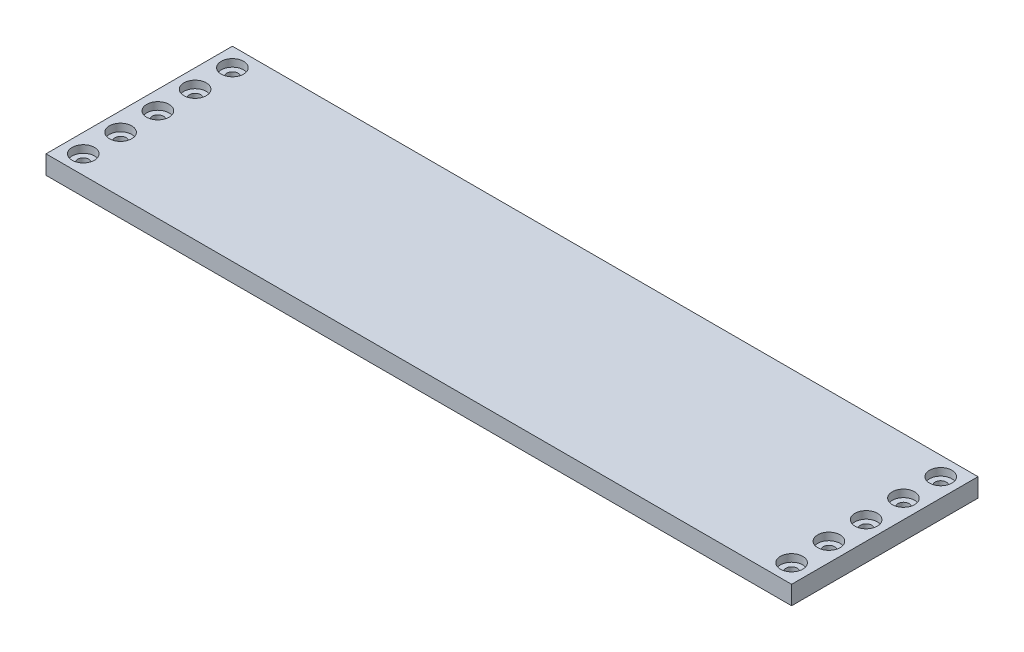
SolidWorks part; units mm, degrees
ref_plane "Front Plane" through (0, 0, 0) normal (0, 0, 1) x (1, 0, 0)
ref_plane "Top Plane" through (0, 0, 0) normal (0, 1, 0) x (1, 0, 0)
ref_plane "Right Plane" through (0, 0, 0) normal (1, 0, 0) x (0, 0, -1)
sketch "Sketch3" plane through (0, 0, 0) normal (0, 1, 0) x (1, 0, 0)
  line L1 (-100, -25) -> (100, -25)
  line L2 (-100, -25) -> (-100, 25)
  line L3 (-100, 25) -> (100, 25)
  line L4 (100, -25) -> (100, 25)
  line L5 (-100, -25) -> (100, 25) construction
  line L6 (-100, 25) -> (100, -25) construction
  point P0 (0, 0)
  dimension "D1" = 50
  dimension "D2" = 200
extrude "Boss-Extrude1" add sketch "Sketch3" along normal blind 5
sketch "Sketch4" plane through (0, 5, 0) normal (0, 1, 0) x (1, 0, 0)
  line L0 (-95, 25) -> (-95, -25) construction
  line L1 (95, 25) -> (95, -25) construction
  line L2 (0, 0) -> (0, 25) construction
  line L4 (100, -25) -> (100, 25)
  line L5 (100, 25) -> (-100, 25)
  line L6 (-100, 25) -> (-100, -25)
  line L7 (-100, -25) -> (100, -25)
  line L8 (100, -25) -> (100, 25)
  line L9 (100, 25) -> (-100, 25)
  line L10 (-100, 25) -> (-100, -25)
  line L11 (-100, -25) -> (100, -25)
  circle A0 centre (-95, 20) radius 1.5
  circle A16 centre (-95, 10) radius 1.5
  circle A17 centre (-95, 0) radius 1.5
  circle A18 centre (-95, -10) radius 1.5
  circle A19 centre (-95, -20) radius 1.5
  circle A22 centre (95, -20) radius 1.5
  circle A23 centre (95, -10) radius 1.5
  circle A24 centre (95, 0) radius 1.5
  circle A25 centre (95, 20) radius 1.5
  circle A26 centre (95, 10) radius 1.5
  circle A27 centre (-95, -30) radius 1.5 [skipped]
  dimension "D4" = 3
  dimension "D5" = 5
  dimension "D2" = 5
  dimension "D3" = 5
  dimension "D6" = 6
  dimension "D7" = 5
  dimension "D1" = 0
extrude "Cut-Extrude1" cut sketch "Sketch4" against normal blind 5
sketch "Sketch5" plane through (0, 5, 0) normal (0, 1, 0) x (1, 0, 0)
  line L1 (-100, -25) -> (100, -25) construction
  circle A0 centre (95, 20) radius 1.5 construction
  circle A1 centre (-95, 20) radius 1.5 construction
  circle A2 centre (95, 20) radius 1.5
  circle A3 centre (-95, 20) radius 1.5
  circle A4 centre (-95, 20) radius 3
  circle A5 centre (95, 20) radius 3
  circle A6 centre (-95, 10) radius 3
  circle A7 centre (95, 10) radius 3
  circle A8 centre (-95, 0) radius 3
  circle A9 centre (95, 0) radius 3
  circle A10 centre (-95, -10) radius 3
  circle A11 centre (95, -10) radius 3
  circle A12 centre (-95, -20) radius 3
  circle A13 centre (95, -20) radius 3
  circle A16 centre (-95, -30) radius 3 [skipped]
  circle A17 centre (95, -30) radius 3 [skipped]
  dimension "D1" = 6
  dimension "D2" = 6
  dimension "D4" = 5
  dimension "D3" = 6
extrude "Cut-Extrude2" cut sketch "Sketch5" against normal blind 2
